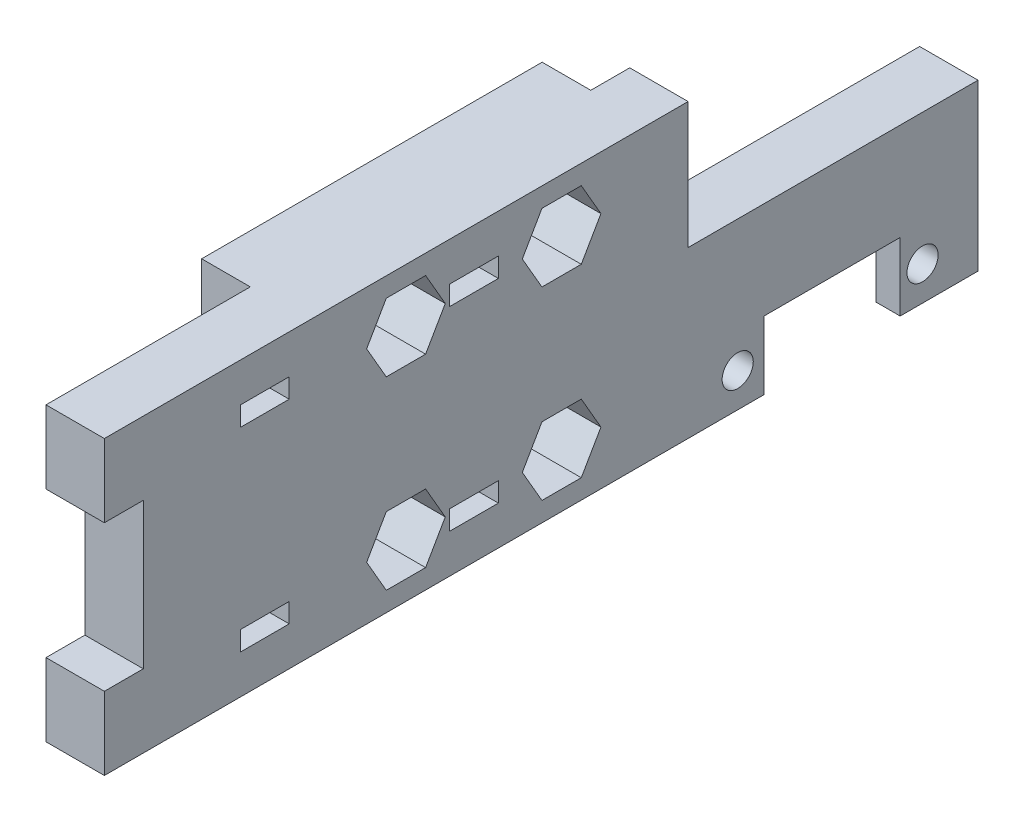
SolidWorks part; units mm, degrees
material "Printed PLA"
ref_plane "Front Plane" through (0, 0, 0) normal (0, 0, 1) x (1, 0, 0)
ref_plane "Top Plane" through (0, 0, 0) normal (0, 1, 0) x (1, 0, 0)
ref_plane "Right Plane" through (0, 0, 0) normal (1, 0, 0) x (0, 0, -1)
sketch "Sketch1" plane through (0, 0, 0) normal (0, 1, 0) x (1, 0, 0)
  line L0 (0, 0) -> (5, 0)
  line L1 (5, 0) -> (5, 19)
  line L2 (0, 0) -> (0, -20)
  line L3 (5, -41) -> (11, -41)
  line L4 (11, 19) -> (11, -41)
  line L5 (5, 19) -> (11, 19)
  line L7 (0, -20) -> (5, -20)
  line L8 (5, -41) -> (5, -20)
  dimension "D1" = 60
  dimension "D2" = 20
  dimension "D3" = 5
  dimension "D4" = 6
  dimension "D5" = 19
extrude "Boss-Extrude1" add sketch "Sketch1" along normal blind 30
sketch "Sketch2" plane through (11, 0, 0) normal (1, 0, 0) x (0, 0, -1)
  line L0 (-10, 5.5) -> (-10, 24.5) construction
  line L1 (-10, 15) -> (19, 15) construction
  line L2 (19, 30) -> (19, 0) construction
  line L3 (0, 30) -> (0, 0) construction
  circle A0 centre (-10, 24.5) radius 2.1
  circle A1 centre (-10, 5.5) radius 2.1
  dimension "D3" = 4.2
  dimension "D1" = 10
  dimension "D2" = 19
extrude "Cut-Extrude1" cut sketch "Sketch2" against normal up to next
sketch "Sketch3" plane through (11, 0, 0) normal (1, 0, 0) x (0, 0, -1)
  line L1 (-14.0415, 24.5) -> (-12.0207, 21)
  line L2 (-12.0207, 21) -> (-7.9793, 21)
  line L3 (-7.9793, 21) -> (-5.9585, 24.5)
  line L4 (-5.9585, 24.5) -> (-7.9793, 28)
  line L5 (-7.9793, 28) -> (-12.0207, 28)
  line L6 (-12.0207, 28) -> (-14.0415, 24.5)
  line L7 (-14.0415, 5.5) -> (-12.0207, 2)
  line L8 (-12.0207, 2) -> (-7.9793, 2)
  line L9 (-7.9793, 2) -> (-5.9585, 5.5)
  line L10 (-5.9585, 5.5) -> (-7.9793, 9)
  line L11 (-7.9793, 9) -> (-12.0207, 9)
  line L12 (-12.0207, 9) -> (-14.0415, 5.5)
  circle A0 centre (-10, 24.5) radius 3.5 construction
  circle A1 centre (-10, 5.5) radius 3.5 construction
  dimension "D1" = 7
extrude "Cut-Extrude2" cut sketch "Sketch3" against normal blind 6
sketch "Sketch4" plane through (11, 0, 0) normal (1, 0, 0) x (0, 0, -1)
  line L0 (-0.5, 5) -> (-5.5, 5) construction
  line L1 (-27, 26) -> (-22, 26)
  line L2 (-27, 26) -> (-27, 24)
  line L3 (-27, 24) -> (-22, 24)
  line L4 (-22, 26) -> (-22, 24)
  line L5 (-27, 6) -> (-22, 6)
  line L6 (-27, 6) -> (-27, 4)
  line L7 (-27, 4) -> (-22, 4)
  line L8 (-22, 6) -> (-22, 4)
  line L9 (-5.5, 26) -> (-0.5, 26)
  line L10 (-5.5, 26) -> (-5.5, 24)
  line L11 (-5.5, 24) -> (-0.5, 24)
  line L12 (-0.5, 26) -> (-0.5, 24)
  line L13 (-5.5, 6) -> (-0.5, 6)
  line L14 (-5.5, 6) -> (-5.5, 4)
  line L15 (-5.5, 4) -> (-0.5, 4)
  line L16 (-0.5, 6) -> (-0.5, 4)
  line L17 (-5.5, 5) -> (-22, 5) construction
  line L18 (-22, 5) -> (-27, 5) construction
  line L19 (-27, 25) -> (-22, 25) construction
  line L20 (-22, 25) -> (-5.5, 25) construction
  line L21 (-5.5, 25) -> (-0.5, 25) construction
  line L22 (-3, 25) -> (-3, 5) construction
  line L23 (-24.5, 25) -> (-24.5, 5) construction
  line L24 (-3, 15) -> (19, 15) construction
  line L25 (19, 30) -> (19, 0) construction
  dimension "D1" = 20
  dimension "D2" = 21.5
  dimension "D3" = 22
  dimension "D4" = 5
  dimension "D5" = 2
extrude "Cut-Extrude3" cut sketch "Sketch4" against normal through all
sketch "Sketch5" plane through (0, 0, 0) normal (-1, 0, 0) x (0, 0, 1)
  line L1 (0.5, 24) -> (5.5, 24)
  line L2 (0.5, 24) -> (0.5, 6)
  line L3 (0.5, 6) -> (5.5, 6)
  line L4 (5.5, 24) -> (5.5, 6)
extrude "Cut-Extrude4" cut sketch "Sketch5" against normal up to surface (5 mm away) up to face at (5, 15, -9.5)
sketch "Sketch6" plane through (5, 0, 0) normal (-1, 0, 0) x (0, 0, 1)
  line L0 (41, 30) -> (41, 0) construction
  line L1 (41, 22.5) -> (37, 22.5)
  line L2 (41, 22.5) -> (41, 7.5)
  line L3 (41, 7.5) -> (37, 7.5)
  line L4 (37, 22.5) -> (37, 7.5)
  line L5 (37, 15) -> (20, 15) construction
  line L6 (20, 30) -> (20, 0) construction
  dimension "D1" = 4
  dimension "D2" = 15
extrude "Cut-Extrude5" cut sketch "Sketch6" against normal through all
sketch "Sketch8" plane through (5, 0, 0) normal (-1, 0, 0) x (0, 0, 1)
  line L0 (0, 30) -> (0, 14.7913)
  line L3 (0, 14.7913) -> (0, 0)
  line L4 (0, 0) -> (-15, 0)
  line L5 (-19, 0) -> (0, 0) construction
  line L6 (-15, 0) -> (-15, 30)
  line L7 (-19, 30) -> (0, 30) construction
  line L8 (-15, 30) -> (0, 30)
  dimension "D1" = 15
extrude "Boss-Extrude2" add sketch "Sketch8" along normal up to surface (5 mm away) up to face at (0, 15, 3)
sketch "Sketch7" plane through (0, 0, 20) normal (0, 0, 1) x (1, 0, 0)
  line L0 (0, 30) -> (0, 0) construction
  line L1 (0, 21) -> (2, 21)
  line L2 (0, 21) -> (0, 9)
  line L3 (0, 9) -> (2, 9)
  line L4 (2, 21) -> (2, 9)
  line L5 (2, 15) -> (11, 15) construction
  line L6 (11, 22.5) -> (11, 7.5) construction
  dimension "D1" = 12
  dimension "D2" = 2
extrude "Cut-Extrude6" cut sketch "Sketch7" against normal through all
pattern_linear "LPattern1" count 2 spacing 16 along (0, 0, -1) of "Cut-Extrude1", "Cut-Extrude2"
sketch "Sketch9" plane through (11, 0, 0) normal (1, 0, 0) x (0, 0, -1)
  line L0 (19, 0) -> (26.8, 0)
  line L1 (26.8, 0) -> (26.8, 7)
  line L2 (26.8, 7) -> (40.8, 7)
  line L3 (40.8, 7) -> (40.8, 0)
  line L4 (40.8, 0) -> (48.8, 0)
  line L5 (48.8, 0) -> (48.8, 17)
  line L6 (48.8, 17) -> (19, 17)
  line L8 (19, 17) -> (19, 0)
  line L9 (19, 30) -> (19, 0) construction
  line L10 (-37, 15) -> (1.5057, 15) construction
  line L12 (-37, 22.5) -> (-37, 7.5) construction
  dimension "D1" = 7.8
  dimension "D2" = 14
  dimension "D3" = 8
  dimension "D4" = 7
  dimension "D5" = 7
  dimension "D6" = 10
extrude "Boss-Extrude3" add sketch "Sketch9" against normal blind 2.5
sketch "Sketch10" plane through (8.5, 0, 0) normal (-1, 0, 0) x (0, 0, 1)
  line L0 (-19, 0) -> (-19, 17) construction
  line L1 (-48.8, 17) -> (-19, 17)
  line L2 (-48.8, 17) -> (-48.8, 8)
  line L3 (-48.8, 8) -> (-19, 8)
  line L4 (-19, 17) -> (-19, 8)
  dimension "D1" = 9
extrude "Boss-Extrude4" add sketch "Sketch10" along normal blind 3.5
sketch "Sketch11" plane through (11, 0, 0) normal (1, 0, 0) x (0, 0, -1)
  line L0 (43.1, 3.5) -> (48.8, 3.5) construction
  line L1 (48.8, 17) -> (48.8, 0) construction
  line L2 (48.8, 0) -> (40.8, 0) construction
  line L3 (24.1, 3.5) -> (43.1, 3.5) construction
  circle A0 centre (43.1, 3.5) radius 1.6
  circle A1 centre (24.1, 3.5) radius 1.6
  dimension "D1" = 3.2
  dimension "D3" = 3.5
  dimension "D2" = 5.7
  dimension "D4" = 19
extrude "Cut-Extrude7" cut sketch "Sketch11" against normal through all
